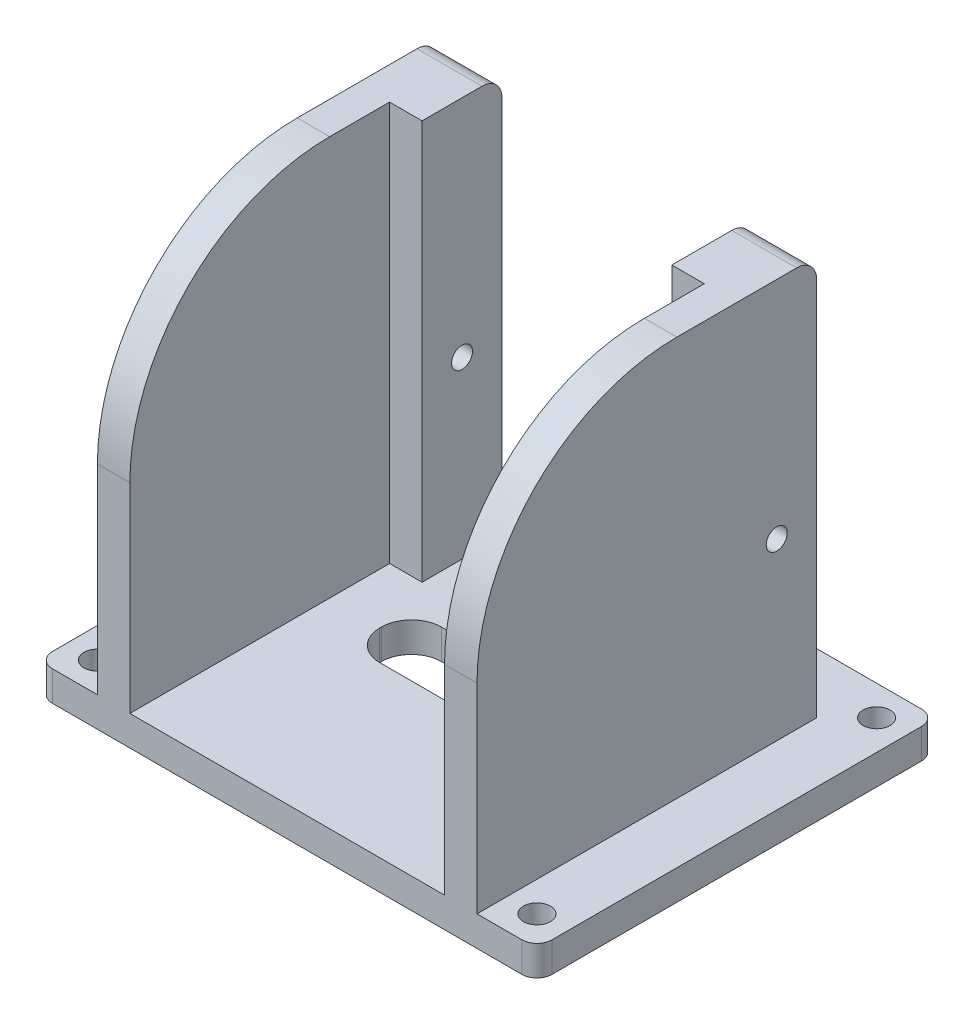
SolidWorks part; units mm, degrees
ref_plane "Płaszczyzna przednia" through (0, 0, 0) normal (0, 0, 1) x (1, 0, 0)
ref_plane "Płaszczyzna górna" through (0, 0, 0) normal (0, 1, 0) x (1, 0, 0)
ref_plane "Płaszczyzna prawa" through (0, 0, 0) normal (1, 0, 0) x (0, 0, -1)
sketch "Szkic1" plane through (0, 0, 0) normal (0, 1, 0) x (1, 0, 0)
  line L1 (-23.5, -20) -> (23.5, -20)
  line L2 (-25, -18.5) -> (-25, 18.5)
  line L3 (-23.5, 20) -> (23.5, 20)
  line L4 (25, -18.5) -> (25, 18.5)
  line L5 (-25, -20) -> (25, 20) construction
  line L6 (-25, 20) -> (25, -20) construction
  arc A4 (23.5, 20) -> (25, 18.5) centre (23.5, 18.5) cw
  arc A5 (25, -18.5) -> (23.5, -20) centre (23.5, -18.5) cw
  arc A6 (-23.5, -20) -> (-25, -18.5) centre (-23.5, -18.5) cw
  arc A7 (-25, 18.5) -> (-23.5, 20) centre (-23.5, 18.5) cw
  point P0 (0, 0)
  dimension "D3" = 1.5
  dimension "D1" = 50
  dimension "D2" = 40
extrude "Dodanie-wyciągnięcie1" add sketch "Szkic1" along normal blind 3
sketch "Szkic2" plane through (0, 3, 0) normal (0, 1, 0) x (1, 0, 0)
  line L0 (7.65, -3.0863) -> (-7.65, -3.0863)
  line L5 (10.65, -0.0863) -> (10.65, 0.0863)
  line L6 (7.65, 3.0863) -> (-7.65, 3.0863)
  line L7 (-10.65, -0.0863) -> (-10.65, 0.0863)
  circle A0 centre (-22, 17) radius 1.35
  circle A1 centre (22, 17) radius 1.35
  circle A2 centre (-22, -17) radius 1.35
  circle A3 centre (22, -17) radius 1.35
  arc A4 (-7.65, 3.0863) -> (-10.65, 0.0863) centre (-7.65, 0.0863) ccw
  arc A5 (-7.65, -3.0863) -> (-10.65, -0.0863) centre (-7.65, -0.0863) cw
  arc A6 (10.65, 0.0863) -> (7.65, 3.0863) centre (7.65, 0.0863) ccw
  arc A7 (7.65, -3.0863) -> (10.65, -0.0863) centre (7.65, -0.0863) ccw
  point P0 (0, 0)
  dimension "D1" = 44
  dimension "D2" = 34
extrude "Wytnij-wyciągnięcie1" cut sketch "Szkic2" against normal blind 3
sketch "Szkic3" plane through (0, 3, 0) normal (0, 1, 0) x (1, 0, 0)
  line L17 (7.65, 3.0863) -> (-7.65, 3.0863) construction
  line L18 (0, 3.0863) -> (0, -3.0863)
  line L19 (-7.65, -3.0863) -> (7.65, -3.0863) construction
  line L42 (-23.5, -20) -> (23.5, -20) construction
  line L46 (-12.5, 6) -> (-12.5, 14)
  line L47 (-12.5, 14) -> (-19, 14)
  line L48 (-19, 14) -> (-19, -20)
  line L49 (-12.5, 6) -> (-15.75, 6)
  line L50 (-15.75, 6) -> (-15.75, -20)
  line L51 (-15.75, -20) -> (-19, -20)
  line L52 (15.75, -20) -> (19, -20)
  line L53 (15.75, 6) -> (15.75, -20)
  line L54 (12.5, 6) -> (15.75, 6)
  line L55 (19, 14) -> (19, -20)
  line L56 (12.5, 14) -> (19, 14)
  line L57 (12.5, 6) -> (12.5, 14)
  line L59 (-25, 18.5) -> (-25, -18.5) construction
  line L60 (23.5, 20) -> (-23.5, 20) construction
  line L61 (-19, -20) -> (-15.75, -20)
  dimension "D1" = 6
  dimension "D2" = 6
  dimension "D3" = 3.25
  dimension "D4" = 8
extrude "Dodanie-wyciągnięcie2" add sketch "Szkic3" along normal blind 40
sketch "Szkic6" plane through (-19, 0, 0) normal (-1, 0, 0) x (0, 0, 1)
  line L0 (-14, 43) -> (-14, 3) construction
  line L1 (-14, 3) -> (20, 3) construction
  circle A0 centre (-10, 20.5) radius 1.05
  dimension "D1" = 4
  dimension "D2" = 17.5
extrude "Wytnij-wyciągnięcie4" cut sketch "Szkic6" against normal through all both and the other way through all
fillet "Zaokrąglenie8" radius 20 1 edges at (-17.375, 43, 20)
fillet "Zaokrąglenie9" radius 20 1 edges at (17.375, 43, 20)
fillet "Zaokrąglenie10" radius 2 1 edges at (-15.75, 43, -14)
fillet "Zaokrąglenie11" radius 2 1 edges at (15.75, 43, -14)
